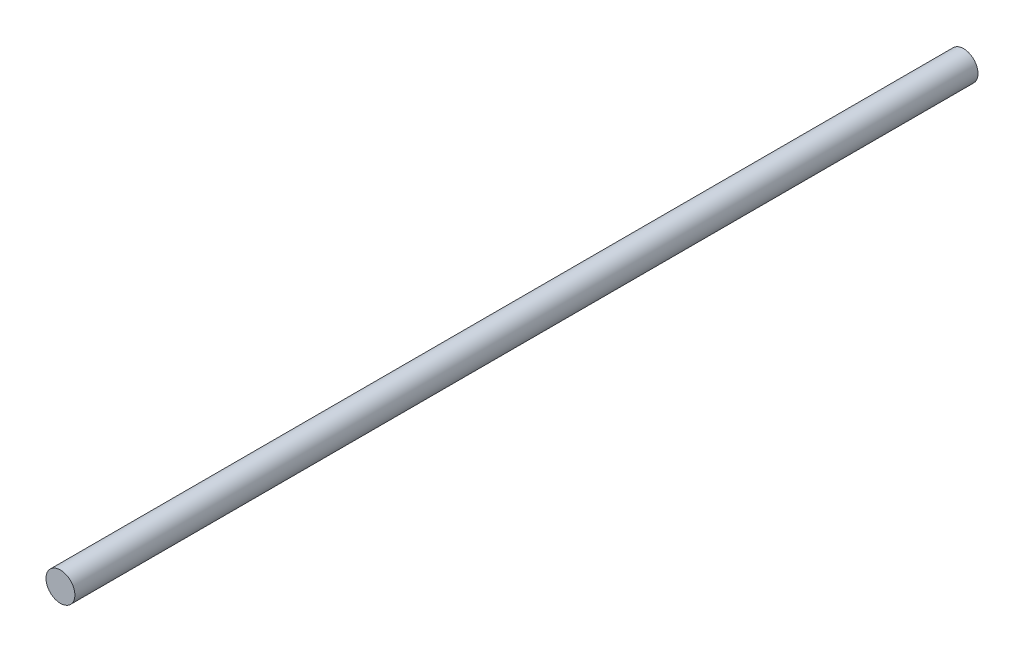
SolidWorks part; units mm, degrees
ref_plane "Alzado" through (0, 0, 0) normal (0, 0, 1) x (1, 0, 0)
ref_plane "Planta" through (0, 0, 0) normal (0, 1, 0) x (1, 0, 0)
ref_plane "Vista lateral" through (0, 0, 0) normal (1, 0, 0) x (0, 0, -1)
sketch "Croquis1" plane through (0, 0, 0) normal (0, 0, 1) x (1, 0, 0)
  circle A0 centre (0, 0) radius 4
extrude "Saliente-Extruir1" add sketch "Croquis1" along normal blind 250
